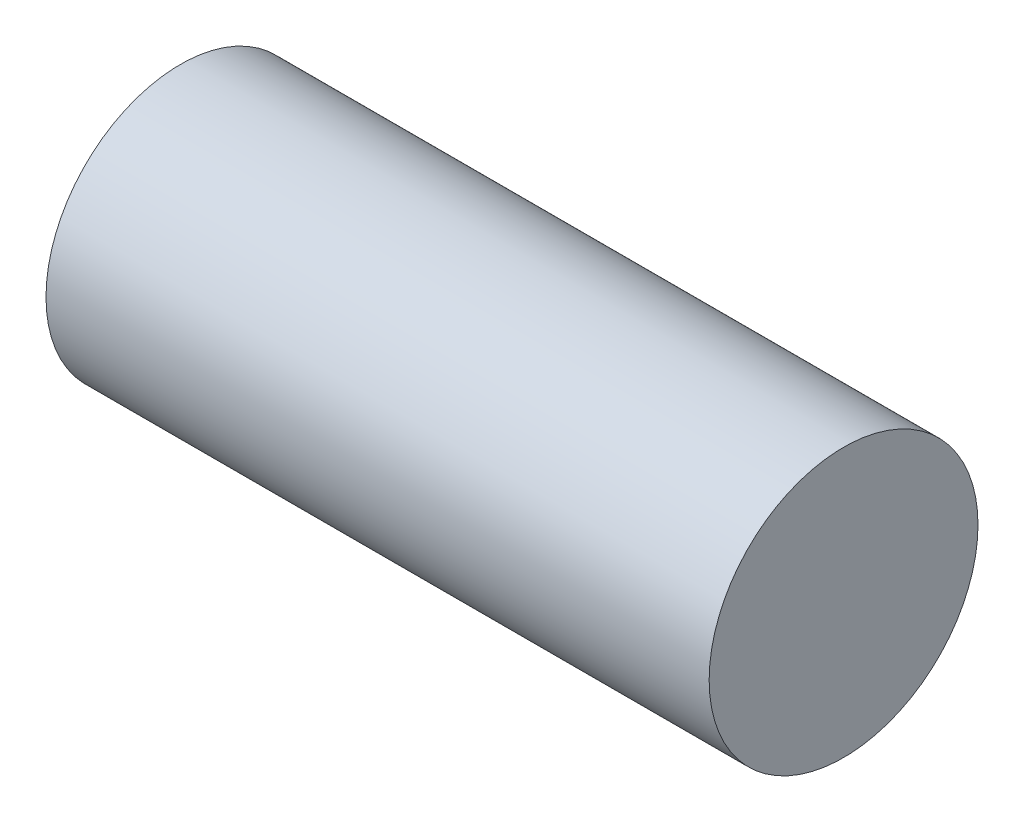
SolidWorks part; units mm, degrees
ref_plane "Front Plane" through (0, 0, 0) normal (0, 0, 1) x (1, 0, 0)
ref_plane "Top Plane" through (0, 0, 0) normal (0, 1, 0) x (1, 0, 0)
ref_plane "Right Plane" through (0, 0, 0) normal (1, 0, 0) x (0, 0, -1)
sketch "Pin Profile" plane through (0, 0, 0) normal (1, 0, 0) x (0, 0, -1)
  circle A0 centre (0, 0) radius 15
  dimension "D1" = 30
extrude "Pin Extrude" add sketch "Pin Profile" against normal blind 74
